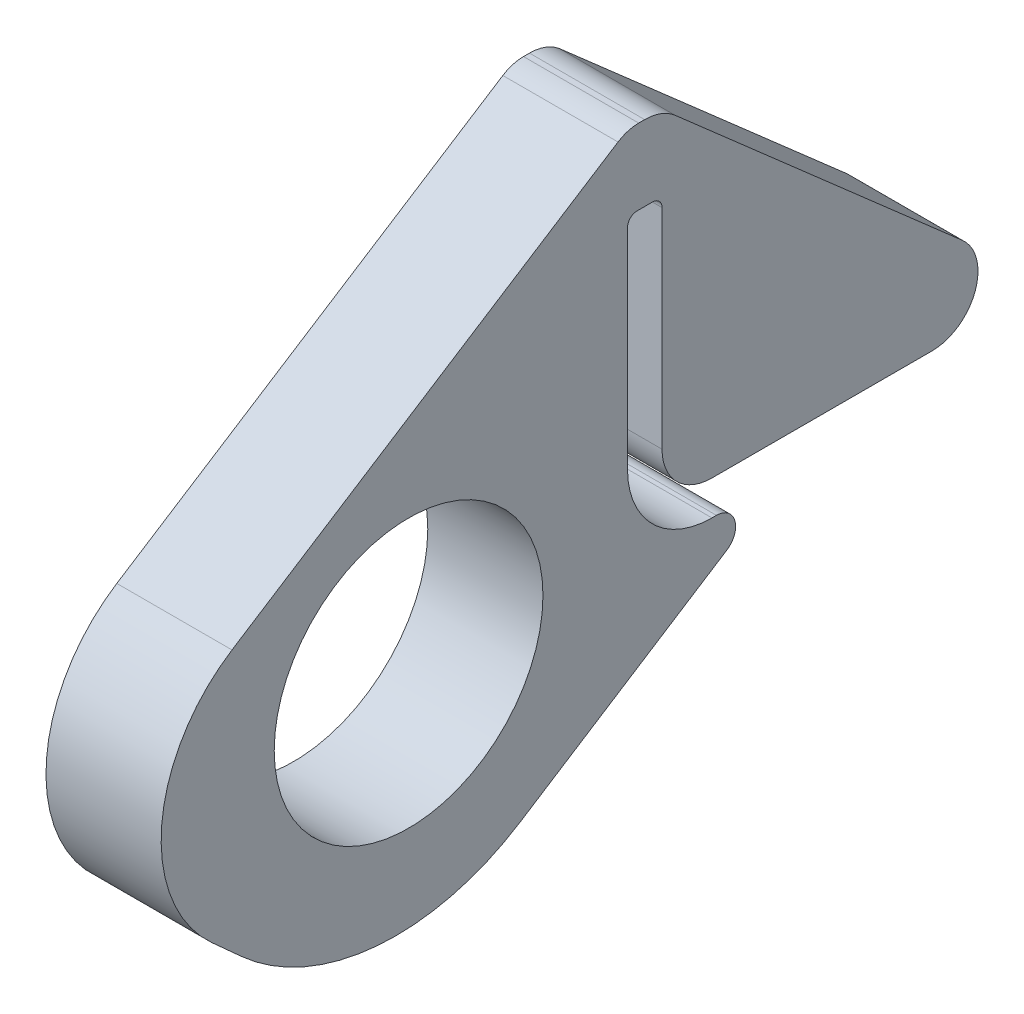
SolidWorks part; units mm, degrees
ref_plane "Front Plane" through (0, 0, 0) normal (0, 0, 1) x (1, 0, 0)
ref_plane "Top Plane" through (0, 0, 0) normal (0, 1, 0) x (1, 0, 0)
ref_plane "Right Plane" through (0, 0, 0) normal (1, 0, 0) x (0, 0, -1)
sketch "Sketch2" plane through (0, 0, 0) normal (1, 0, 0) x (0, 0, -1)
  line L0 (0, 0) -> (0, 7.5) construction
  line L1 (0, 0) -> (50, 0) construction
  line L2 (0, 7.5) -> (0.5, 7.5) construction
  line L3 (0, 0) -> (0, 0.5) construction
  line L4 (0, 0.5) -> (6.6281, 0.5) construction
  line L5 (0.5, 7.5) -> (0.5, 2)
  line L6 (2, 0.5) -> (10.9184, 0.5)
  line L7 (0.5, 7.5) -> (0, 7.5)
  line L8 (0, 7.5) -> (0, 2)
  line L9 (2, 0) -> (10.9184, 0)
  line L10 (10.9184, 0) -> (10.9184, 0.5)
  arc A0 (0.5, 2) -> (2, 0.5) centre (2, 2) ccw
  arc A1 (0, 2) -> (2, 0) centre (2, 2) ccw
  point P12 (0.5, 0.5)
  dimension "D5" = 1.5
  dimension "D6" = 2
  dimension "D1" = 7.5
  dimension "D2" = 50
  dimension "D3" = 0.5
  dimension "D4" = 0.5
sketch "Sketch3" plane through (0, 0, 0) normal (1, 0, 0) x (0, 0, -1)
  line L0 (10.9184, 0.5) -> (10.9184, 0.7) construction
  line L1 (10.9184, 0) -> (10.9184, -0.2) construction
  line L2 (7.7298, 0.7) -> (2, 0.7)
  line L3 (0.5, 2) -> (0.7, 2) construction
  line L4 (0.7, 2) -> (0.7, 7.45)
  line L5 (0.45, 7.7) -> (0.05, 7.7)
  line L6 (-0.2, 7.45) -> (-0.2, 2)
  line L7 (3.827, 0) -> (3.827, -0.2) construction
  line L8 (2, 0) -> (10.9184, 0) construction
  line L9 (2.1171, -0.2) -> (2, -0.2)
  line L10 (8.521, 2.8022) -> (1.0396, 9.3626)
  line L11 (0.2484, 9.6604) -> (0.0924, 9.6604)
  line L12 (-0.4463, 9.5028) -> (-10.5009, 3.0728)
  line L13 (2.3864, -1.1212) -> (-3.0002, -4.5661)
  line L14 (-10.2569, -3.9618) -> (-11.0286, -3.264)
  line L15 (4.7031, 0.5) -> (4.7031, 0.25) construction
  line L16 (2, 0.5) -> (10.9184, 0.5) construction
  line L17 (4.2753, 0.25) -> (5.131, 0.25) construction
  arc A0 (0.7, 2) -> (2, 0.7) centre (2, 2) ccw
  arc A1 (-0.2, 2) -> (2, -0.2) centre (2, 2) ccw
  circle A2 centre (-5.9011, 0.25) radius 3.5
  arc A3 (-10.5009, 3.0728) -> (-11.0286, -3.264) centre (-8.3459, -0.297) ccw
  arc A4 (-3.0002, -4.5661) -> (-10.2569, -3.9618) centre (-6.2328, 0.4887) cw
  arc A5 (0.0924, 9.6604) -> (-0.4463, 9.5028) centre (0.0924, 8.6604) ccw
  arc A6 (1.0396, 9.3626) -> (0.2484, 9.6604) centre (0.2484, 8.4604) ccw
  arc A7 (8.521, 2.8022) -> (7.7298, 0.7) centre (7.7298, 1.9) cw
  arc A8 (2.1171, -0.2) -> (2.3864, -1.1212) centre (2.1171, -0.7) cw
  arc A9 (0.7, 7.45) -> (0.45, 7.7) centre (0.45, 7.45) ccw
  arc A10 (0.05, 7.7) -> (-0.2, 7.45) centre (0.05, 7.45) ccw
  point P31 (4.7031, 0.25)
  point P36 (-5.9011, 0.25)
  point P39 (0.7, 7.7)
  point P44 (-14.915, 0.25)
  point P54 (0, 0)
  dimension "D3" = 0.2
  dimension "D4" = 5.7
  dimension "D5" = 0.25
  dimension "D6" = 7
  dimension "D7" = 4
  dimension "D8" = 6
  dimension "D9" = 1
  dimension "D10" = 1.2
  dimension "D11" = 1.2
  dimension "D12" = 0.5
  dimension "D13" = 0.25
  dimension "D1" = 0.2
  dimension "D2" = 0.2
extrude "Boss-Extrude1" add sketch "Sketch3" along normal blind 3
